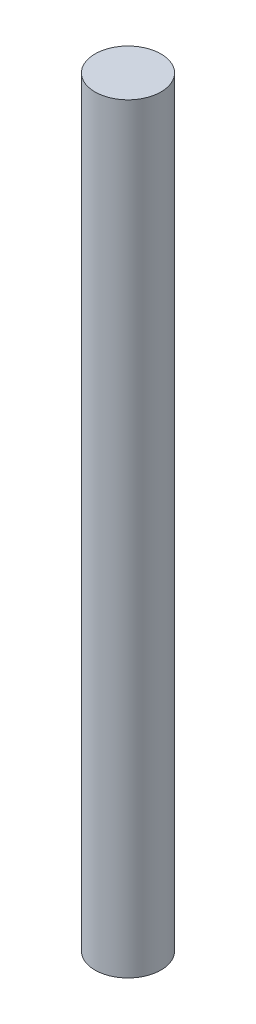
SolidWorks part; units mm, degrees
ref_plane "Front Plane" through (0, 0, 0) normal (0, 0, 1) x (1, 0, 0)
ref_plane "Top Plane" through (0, 0, 0) normal (0, 1, 0) x (1, 0, 0)
ref_plane "Right Plane" through (0, 0, 0) normal (1, 0, 0) x (0, 0, -1)
sketch "Sketch1" plane through (0, 0, 0) normal (0, 1, 0) x (1, 0, 0)
  circle A0 centre (0, 0) radius 3.4365
  dimension "D1" = 6.873
extrude "Boss-Extrude1" add sketch "Sketch1" along normal blind 79.278
